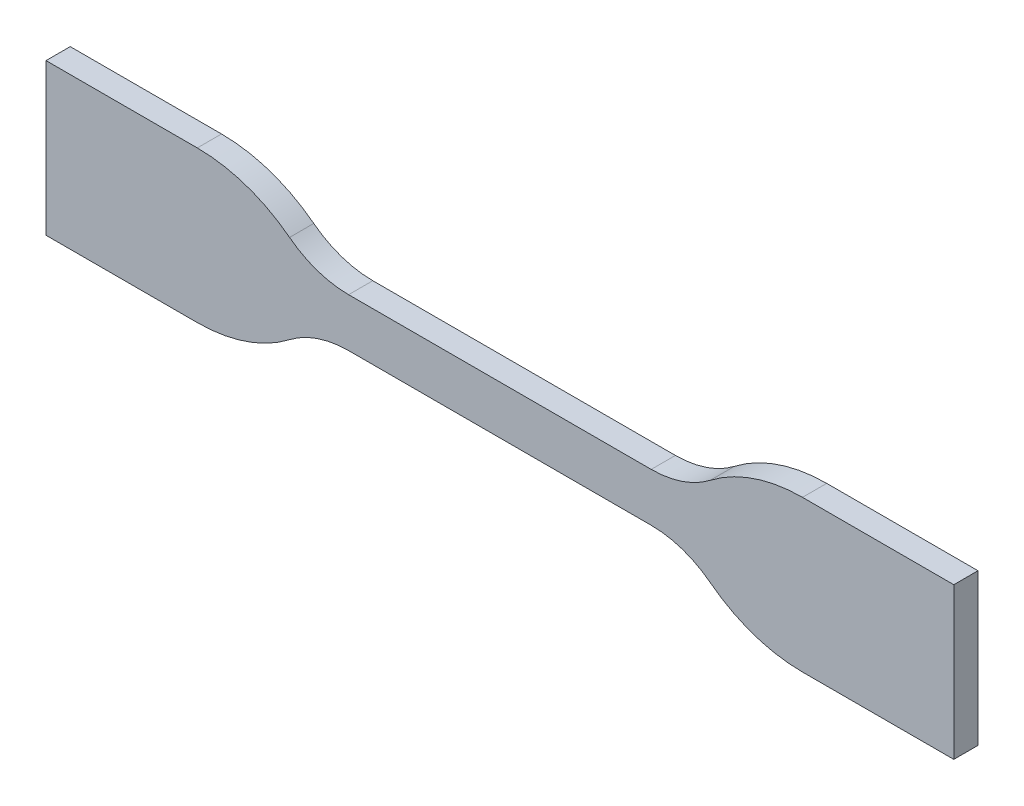
SolidWorks part; units mm, degrees
ref_plane "Front Plane" through (0, 0, 0) normal (0, 0, 1) x (1, 0, 0)
ref_plane "Top Plane" through (0, 0, 0) normal (0, 1, 0) x (1, 0, 0)
ref_plane "Right Plane" through (0, 0, 0) normal (1, 0, 0) x (0, 0, -1)
sketch "Sketch1" plane through (0, 0, 0) normal (0, 0, 1) x (1, 0, 0)
  line L0 (0, 0) -> (0, 44.0854) construction
  line L1 (-97.1951, 0) -> (97.1951, 0) construction
  line L2 (-12.5, 2) -> (12.5, 2)
  line L3 (25, 6.25) -> (37.5, 6.25)
  line L4 (37.5, 6.25) -> (37.5, -6.25)
  line L7 (-25, -6.25) -> (-37.5, -6.25)
  line L8 (-37.5, 6.25) -> (-37.5, -6.25)
  line L9 (-25, 6.25) -> (-37.5, 6.25)
  line L10 (12.5, 2) -> (12.5, 11.3183) construction
  line L11 (-12.5, -2) -> (12.5, -2)
  line L12 (25, -6.25) -> (37.5, -6.25)
  line L13 (10, 2) -> (10, 6.25) construction
  line L14 (-10, 2) -> (-10, 6.25) construction
  arc A1 (25, 6.25) -> (17.3783, 3.6586) centre (25, -6.254) ccw
  arc A2 (12.5, 2) -> (17.3783, 3.6586) centre (12.5, 10.0034) ccw
  arc A3 (12.5, -2) -> (17.3783, -3.6586) centre (12.5, -10.0034) cw
  arc A4 (25, -6.25) -> (17.3783, -3.6586) centre (25, 6.254) cw
  arc A5 (-12.5, 2) -> (-17.3783, 3.6586) centre (-12.5, 10.0034) cw
  arc A6 (-25, 6.25) -> (-17.3783, 3.6586) centre (-25, -6.254) cw
  arc A7 (-12.5, -2) -> (-17.3783, -3.6586) centre (-12.5, -10.0034) ccw
  arc A8 (-25, -6.25) -> (-17.3783, -3.6586) centre (-25, 6.254) ccw
  point P3 (-25, -14.5)
  point P11 (25, 14.5)
  point P15 (37.5, 0)
  point P16 (25, -14.5)
  point P24 (0, -2)
  point P26 (0, 2)
  point P27 (-37.5, 0)
  point P28 (-25, 14.5)
  dimension "D2" = 50
  dimension "D5" = 75
  dimension "D6" = 12.5
  dimension "D7" = 12.504
  dimension "D8" = 8.0034
  dimension "D1" = 25
  dimension "D3" = 12.5
  dimension "D4" = 4
  dimension "D10" = 20
extrude "Boss-Extrude1" add sketch "Sketch1" along normal blind 2
